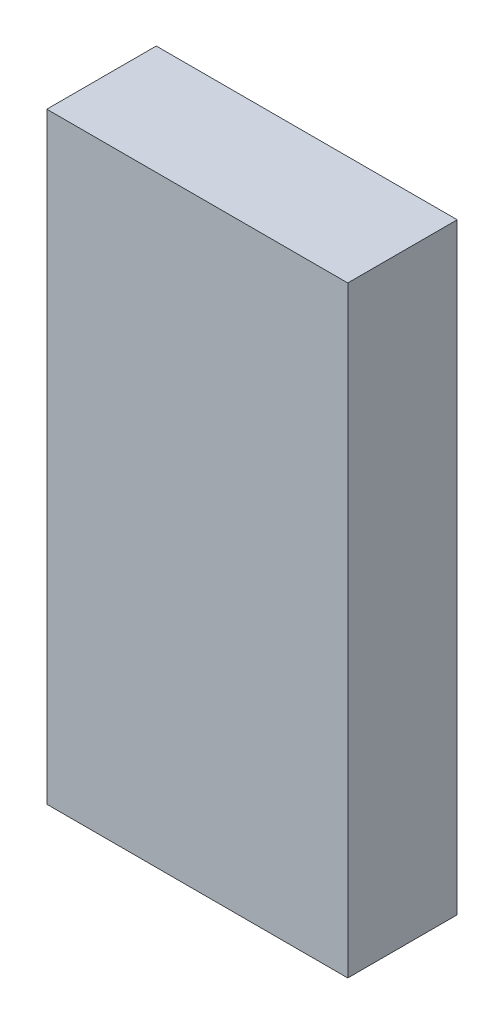
SolidWorks part; units mm, degrees
ref_plane "Front" through (0, 0, 0) normal (0, 0, 1) x (1, 0, 0)
ref_plane "Top" through (0, 0, 0) normal (0, 1, 0) x (1, 0, 0)
ref_plane "Right" through (0, 0, 0) normal (1, 0, 0) x (0, 0, -1)
sketch "ｽｹｯﾁ1" plane through (0, 0, 0) normal (0, 0, 1) x (1, 0, 0)
  line L1 (-55, -110) -> (55, -110)
  line L2 (-55, -110) -> (-55, 110)
  line L3 (-55, 110) -> (55, 110)
  line L4 (55, -110) -> (55, 110)
  line L5 (-55, -110) -> (55, 110) construction
  line L6 (-55, 110) -> (55, -110) construction
  point P0 (0, 0)
  dimension "D1" = 110
  dimension "D2" = 220
extrude "ﾎﾞｽ - 押し出し1" add sketch "ｽｹｯﾁ1" along normal blind 40
